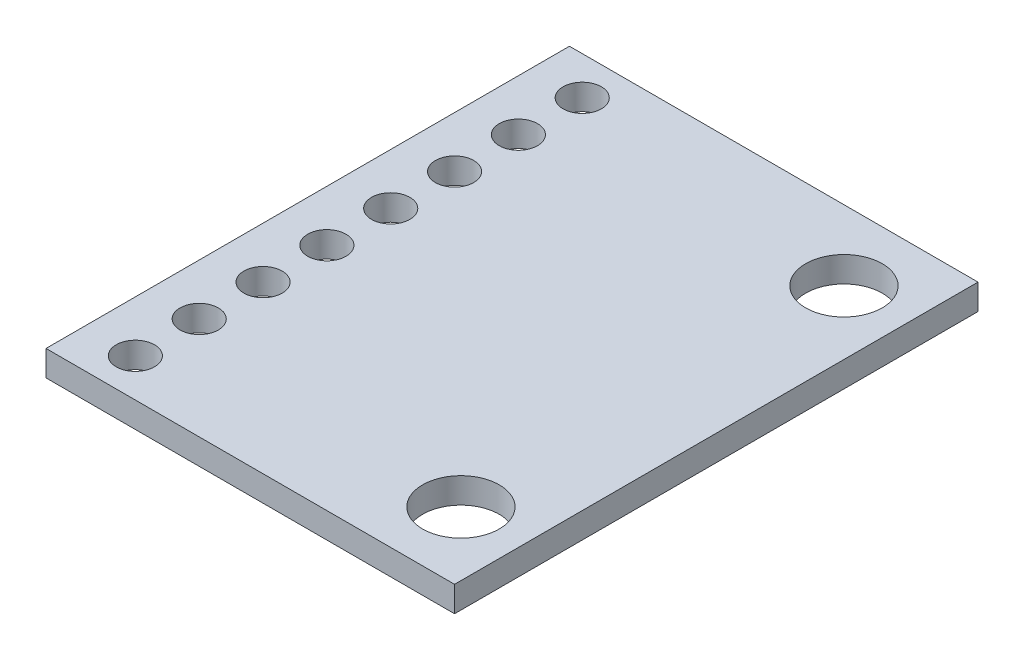
SolidWorks part; units mm, degrees
ref_plane "Front Plane" through (0, 0, 0) normal (0, 0, 1) x (1, 0, 0)
ref_plane "Top Plane" through (0, 0, 0) normal (0, 1, 0) x (1, 0, 0)
ref_plane "Right Plane" through (0, 0, 0) normal (1, 0, 0) x (0, 0, -1)
sketch "Sketch1" plane through (0, 0, 0) normal (0, 1, 0) x (1, 0, 0)
  line L1 (-8, -10.25) -> (8, -10.25)
  line L2 (-8, -10.25) -> (-8, 10.25)
  line L3 (-8, 10.25) -> (8, 10.25)
  line L4 (8, -10.25) -> (8, 10.25)
  line L5 (-8, -10.25) -> (8, 10.25) construction
  line L6 (-8, 10.25) -> (8, -10.25) construction
  circle A0 centre (5.5, 7.5) radius 1.5
  circle A1 centre (5.5, -7.5) radius 1.5
  point P0 (0, 0)
  point P10 (-6.2078, 8.6932)
  point P11 (0, 0)
  dimension "D3" = 3
  dimension "D1" = 16
  dimension "D2" = 20.5
  dimension "D4" = 2.5
  dimension "D5" = 2.75
  dimension "D6" = 15
extrude "Boss-Extrude1" add sketch "Sketch1" along normal blind 1
sketch "Sketch2" plane through (0, 1, 0) normal (0, 1, 0) x (1, 0, 0)
  line L4 (8, -10.25) -> (8, 10.25)
  line L5 (8, 10.25) -> (-8, 10.25)
  line L6 (-8, 10.25) -> (-8, -10.25)
  line L7 (-8, -10.25) -> (8, -10.25)
  line L8 (8, -10.25) -> (8, 10.25)
  line L9 (8, 10.25) -> (-8, 10.25)
  line L10 (-8, 10.25) -> (-8, -10.25)
  line L11 (-8, -10.25) -> (8, -10.25)
  circle A0 centre (-6, 8.75) radius 0.75
  circle A1 centre (-6, 6.25) radius 0.75
  circle A2 centre (-6, 3.75) radius 0.75
  circle A3 centre (-6, 1.25) radius 0.75
  circle A4 centre (-6, -1.25) radius 0.75
  circle A5 centre (-6, -3.75) radius 0.75
  circle A6 centre (-6, -6.25) radius 0.75
  circle A7 centre (-6, -8.75) radius 0.75
  dimension "D2" = 1.5
  dimension "D3" = 2
  dimension "D5" = 1.5
  dimension "D6" = 1.5
  dimension "D1" = 0
  dimension "D4" = 8
extrude "Cut-Extrude2" cut sketch "Sketch2" against normal through all contours A0 | A1 | A2 | A3 | A4 | A5 | A6 | A7
